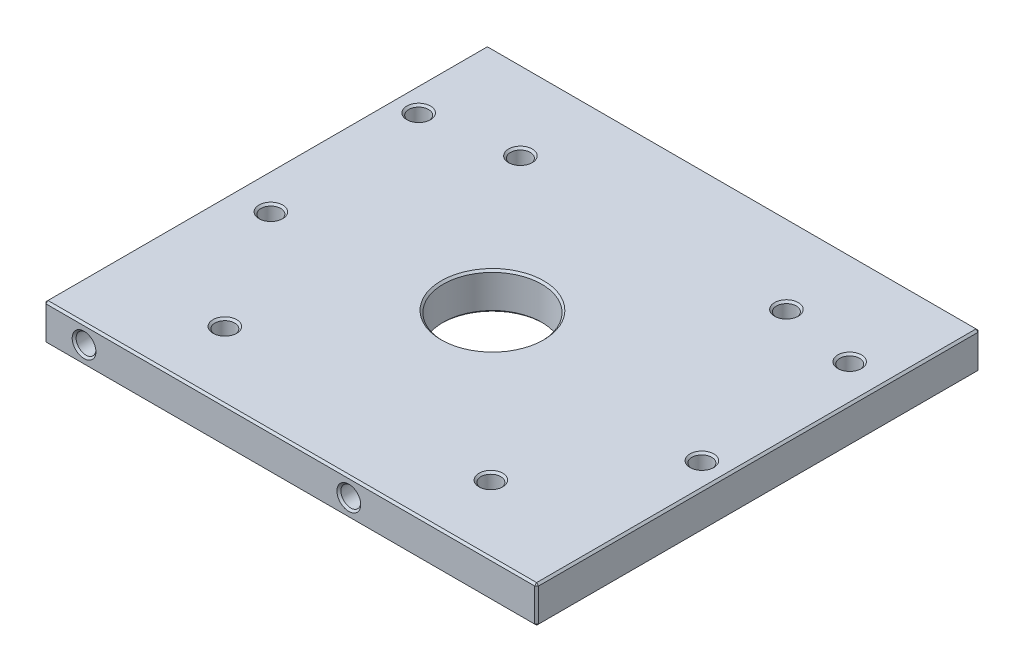
SolidWorks part; units mm, degrees
material "6061 Alloy"
ref_plane "Front Plane" through (0, 0, 0) normal (0, 0, 1) x (1, 0, 0)
ref_plane "Top Plane" through (0, 0, 0) normal (0, 1, 0) x (1, 0, 0)
ref_plane "Right Plane" through (0, 0, 0) normal (1, 0, 0) x (0, 0, -1)
sketch "Sketch1" plane through (0, 0, 0) normal (0, 1, 0) x (1, 0, 0)
  line L1 (-63.5, 57.15) -> (63.5, 57.15)
  line L2 (-63.5, 57.15) -> (-63.5, -57.15)
  line L3 (-63.5, -57.15) -> (63.5, -57.15)
  line L4 (63.5, 57.15) -> (63.5, -57.15)
  line L5 (-63.5, 57.15) -> (63.5, -57.15) construction
  line L6 (-63.5, -57.15) -> (63.5, 57.15) construction
  point P0 (0, 0)
  dimension "D1" = 114.3
  dimension "D2" = 127
extrude "Boss-Extrude1" add sketch "Sketch1" along normal blind 9.525
sketch "Sketch2" plane through (0, 9.525, 0) normal (0, 1, 0) x (1, 0, 0)
  line L2 (63.5, 57.15) -> (-63.5, 57.15) construction
  circle A0 centre (-3.4925, -1.5494) radius 12.7
  dimension "D1" = 25.4
  dimension "D2" = 58.6994
  dimension "D3" = 3.4925
extrude "Cut-Extrude1" cut sketch "Sketch2" against normal through all
hole_wizard "#10 Clearance Hole2" positions "Sketch4" profile "Sketch3" hole size "#10" standard "ANSI Inch"
sketch "Sketch4" plane through (1.0143, 0, 37.6595) normal (0, 1, 0) x (1, 0, 0)
  line L1 (-35.3958, 74.2101) -> (33.1842, 74.2101) construction
  line L2 (-35.3958, 74.2101) -> (-35.3958, -1.9899) construction
  line L3 (-35.3958, -1.9899) -> (33.1842, -1.9899) construction
  line L4 (33.1842, 74.2101) -> (33.1842, -1.9899) construction
  line L5 (-1.1058, 74.2101) -> (-1.1058, 94.8095) construction
  line L8 (62.4857, 94.8095) -> (-64.5143, 94.8095) construction
  line L9 (-4.5068, 36.1101) -> (33.1842, 36.1101) construction
  point P1 (-35.3958, 74.2101)
  point P2 (33.1842, -1.9899)
  point P151 (-35.3958, -1.9899)
  point P152 (33.1842, 74.2101)
  dimension "D1" = 68.58
  dimension "D2" = 76.2
  dimension "D3" = 20.5994
  dimension "D4" = 37.6911
sketch "Sketch3" plane through (-34.3814, 0, -36.5506) normal (1, 0, 0) x (0, 0, -1)
  line L0 (0, 0) -> (0, 39.6338)
  line L1 (0, 39.6338) -> (2.5527, 38.1)
  line L2 (2.5527, 38.1) -> (2.5527, 0)
  line L5 (2.5527, 0) -> (0, 0)
  line L10 (0, 39.6338) -> (-2.5527, 38.1) construction
  line L11 (0, -6.35) -> (0, 107.95) construction
  dimension "Hole Dia." = 5.1054
  dimension "Hole Depth" = 38.1
  dimension "Drill Angle" = 118
hole_wizard "#10 Clearance Hole3" positions "Sketch6" profile "Sketch5" hole size "#10" standard "ANSI Inch" end condition through all
sketch "Sketch6" plane through (0, 0, 0) normal (0, -1, 0) x (-1, 0, 0)
  line L0 (-54.0385, -57.15) -> (-54.0385, 57.15) construction
  line L1 (63.5, -57.15) -> (-63.5, -57.15) construction
  line L2 (-63.5, 57.15) -> (63.5, 57.15) construction
  line L7 (-63.5, -57.15) -> (-63.5, 57.15) construction
  line L9 (-54.0385, 33.02) -> (-57.0865, -8.128) construction
  line L10 (57.0865, 57.15) -> (57.0865, -57.15) construction
  line L11 (-63.5, 57.15) -> (63.5, 57.15) construction
  line L12 (63.5, -57.15) -> (-63.5, -57.15) construction
  line L14 (57.0865, 33.02) -> (54.0385, -8.128) construction
  line L15 (63.5, 57.15) -> (63.5, -57.15) construction
  point P560 (-54.0385, 33.02)
  point P578 (-57.0865, -8.128)
  point P598 (57.0865, 33.02)
  point P599 (54.0385, -8.128)
  dimension "D1" = 24.13
  dimension "D2" = 9.4615
  dimension "D3" = 3.048
  dimension "D4" = 41.148
  dimension "D5" = 24.13
  dimension "D6" = 3.048
  dimension "D7" = 6.4135
  dimension "D9" = 41.148
sketch "Sketch5" plane through (54.0385, 0, -33.02) normal (1, 0, 0) x (0, 0, -1)
  line L0 (0, 0) -> (0, 9.525)
  line L1 (0, 9.525) -> (2.5527, 9.525)
  line L2 (2.5527, 9.525) -> (2.5527, 0)
  line L5 (2.5527, 0) -> (0, 0)
  line L11 (0, -6.35) -> (0, 107.95) construction
  dimension "Thru Hole Dia." = 5.1054
  dimension "Thru Hole Depth" = 9.525
hole_wizard "Tapped Hole for #10-32 Helicoil1" positions "Sketch8" profile "Sketch7" tap size "#10-32" standard "Helicoil® Inch"
sketch "Sketch8" plane through (0, 0, 57.15) normal (0, 0, 1) x (1, 0, 0)
  line L1 (-53.1812, 4.7625) -> (15.0813, 4.7625) construction
  line L4 (-19.05, 4.7625) -> (-19.05, 0) construction
  line L6 (-63.5, 9.525) -> (-63.5, 0) construction
  line L7 (-63.5, 0) -> (63.5, 0) construction
  point P10 (-53.1812, 4.7625)
  point P12 (15.0813, 4.7625)
  dimension "D1" = 4.7625
  dimension "D2" = 68.2625
  dimension "D3" = 44.45
sketch "Sketch7" plane through (-53.1812, 4.7625, 57.15) normal (1, 0, 0) x (0, -1, 0)
  line L0 (0, 0) -> (0, 26.9338)
  line L1 (0, 26.9338) -> (2.5527, 25.4)
  line L2 (2.5527, 25.4) -> (2.5527, 0)
  line L5 (2.5527, 0) -> (0, 0)
  line L10 (0, 26.9338) -> (-2.5527, 25.4) construction
  line L11 (0, -6.35) -> (0, 107.95) construction
  dimension "Tap Drill Dia." = 5.1054
  dimension "Tap Drill Depth" = 25.4
  dimension "Drill Angle" = 118
chamfer "Chamfer1" distance 0.508 angle 45 32 edges at (17.634, 4.7625, 57.15) (-50.6285, 4.7625, 57.15) (-3.4925, 0, 14.2494) (34.1986, 0, -39.1033) (-34.3814, 0, 37.0967) (34.1986, 0, 37.0967) (-34.3814, 0, -39.1033) (-54.0385, 0, 5.5753) (-57.0865, 0, -35.5727) (57.0865, 0, 5.5753) (54.0385, 0, -35.5727) (-63.5, 4.7625, -57.15) (-63.5, 4.7625, 57.15) (63.5, 4.7625, 57.15) (0, 0, -57.15) (-63.5, 0, 0) (0, 0, 57.15) (63.5, 0, 0) (63.5, 4.7625, -57.15) (0, 9.525, 57.15) (-63.5, 9.525, 0) (0, 9.525, -57.15) (63.5, 9.525, 0) (-3.4925, 9.525, 14.2494) (34.1986, 9.525, -33.9979) (-34.3814, 9.525, 42.2021) (34.1986, 9.525, 42.2021) (-34.3814, 9.525, -33.9979) (-54.0385, 9.525, 5.5753) (-57.0865, 9.525, -35.5727) (57.0865, 9.525, 5.5753) (54.0385, 9.525, -35.5727)
